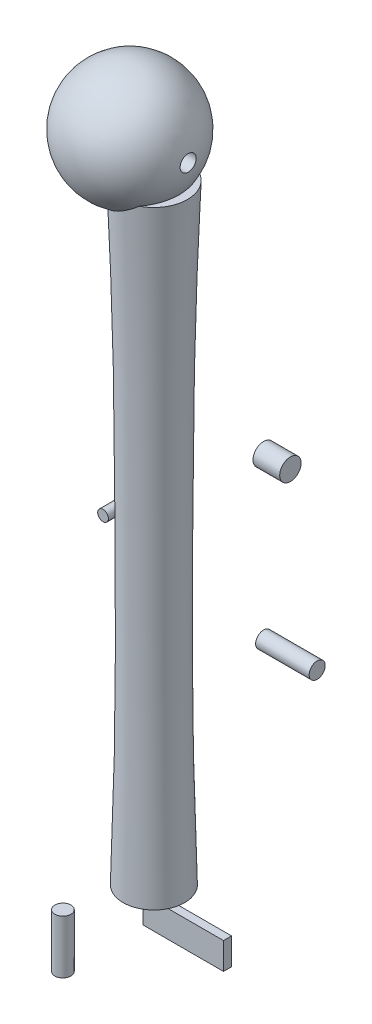
SolidWorks part; units mm, degrees
material "Nylon 101"
ref_plane "Alzado" through (0, 0, 0) normal (0, 0, 1) x (1, 0, 0)
ref_plane "Planta" through (0, 0, 0) normal (0, 1, 0) x (1, 0, 0)
ref_plane "Vista lateral" through (0, 0, 0) normal (1, 0, 0) x (0, 0, -1)
sketch "Sketch1" plane through (0, 0, 0) normal (0, 0, 1) x (1, 0, 0)
  line L0 (20.5, -240) -> (9, -240)
  line L1 (9, -240) -> (9, -12)
  line L2 (9, -12) -> (21.5, -12)
  line L3 (9, -244) -> (9, -8) construction
  spline S0 degree 3 poles (21.5, -12) (21.0197, -24.6656) (19.655, -60.6507) (19.2605, -123.3313) (18.9696, -186.6777) (20.1173, -226.6674) (20.5, -240) knots 0 0 0 0 0.166734 0.473722 0.824538 1 1 1 1
revolve "Diafisis" add sketch "Sketch1" angle 360 about L3
sketch "Sketch2" plane through (0, 0, 0) normal (0, 0, 1) x (1, 0, 0)
  line L0 (0, -22) -> (0, 22)
  line L1 (0, -26) -> (0, 26) construction
  arc A0 (0, 22) -> (0, -22) centre (0, 0) cw
revolve "Cabeza" add sketch "Sketch2" angle 360 about L1
ref_plane "Plane2" through (0, 0, -8) normal (0, 0, 1) x (1, 0, 0)
sketch "Sketch3" plane through (0, 0, -8) normal (0, 0, 1) x (1, 0, 0)
  line L0 (0, -260) -> (30, -260)
  line L1 (30, -260) -> (30, -250)
  line L2 (30, -250) -> (0, -250)
  line L3 (0, -250) -> (0, -260)
extrude "PlacaFrontal" add sketch "Sketch3" along normal blind 3
ref_plane "Plane3" through (30, 0, 0) normal (1, 0, 0) x (0, 0, -1)
sketch "Sketch4" plane through (30, 0, 0) normal (1, 0, 0) x (0, 0, -1)
  circle A0 centre (20, -100) radius 4
extrude "CilLateral" add sketch "Sketch4" along normal blind 10
ref_plane "Plane5" through (0, -300, 0) normal (0, 1, 0) x (1, 0, 0)
sketch "Sketch5" plane through (0, -300, 0) normal (0, 1, 0) x (1, 0, 0)
  circle A0 centre (-40, 15) radius 3
extrude "CilSuperior" add sketch "Sketch5" along normal blind 20
ref_plane "Plane7" through (0, 0, -10) normal (0, 0, 1) x (1, 0, 0)
sketch "Sketch6" plane through (0, 0, -10) normal (0, 0, 1) x (1, 0, 0)
  line L0 (40, -150) -> (40, -147)
  line L1 (40, -147) -> (60, -147)
  line L2 (60, -147) -> (60, -150)
  line L3 (60, -150) -> (40, -150)
  line L4 (36, -150) -> (64, -150) construction
revolve "RevX" add sketch "Sketch6" angle 360 about L4
ref_plane "Plane9" through (-30, 0, 0) normal (1, 0, 0) x (0, 0, -1)
sketch "Sketch7" plane through (-30, 0, 0) normal (1, 0, 0) x (0, 0, -1)
  line L0 (20, -150) -> (20, -148)
  line L1 (20, -148) -> (35, -148)
  line L2 (35, -148) -> (35, -150)
  line L3 (35, -150) -> (20, -150)
  line L4 (16, -150) -> (39, -150) construction
revolve "RevA" add sketch "Sketch7" angle 360 about L4
sketch "Sketch8" plane through (0, 0, 0) normal (1, 0, 0) x (0, 0, -1)
  circle A0 centre (0, 0) radius 3
extrude "Taladro" cut sketch "Sketch8" against normal mid plane 2000
